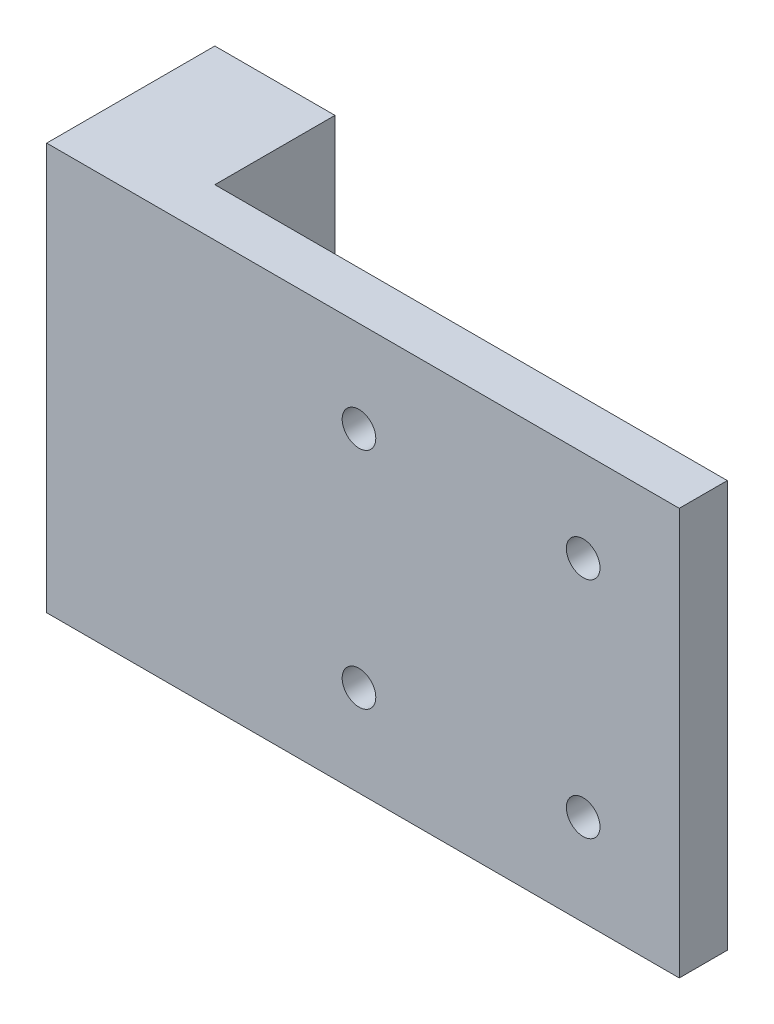
SolidWorks part; units mm, degrees
ref_plane "Front Plane" through (0, 0, 0) normal (0, 0, 1) x (1, 0, 0)
ref_plane "Top Plane" through (0, 0, 0) normal (0, 1, 0) x (1, 0, 0)
ref_plane "Right Plane" through (0, 0, 0) normal (1, 0, 0) x (0, 0, -1)
sketch "Sketch1" plane through (0, 0, 0) normal (0, 0, 1) x (1, 0, 0)
  line L1 (0, 0) -> (79, 0)
  line L2 (0, 0) -> (0, 50.8)
  line L3 (0, 50.8) -> (79, 50.8)
  line L4 (79, 0) -> (79, 50.8)
  circle A0 centre (67, 39.4) radius 2.1
  circle A1 centre (67, 11.4) radius 2.1
  circle A2 centre (39, 39.4) radius 2.1
  circle A3 centre (39, 11.4) radius 2.1
  dimension "D4" = 4.2
  dimension "D5" = 4.2
  dimension "D8" = 4.2
  dimension "D9" = 4.2
  dimension "D1" = 50.8
  dimension "D2" = 79
  dimension "D3" = 12
  dimension "D6" = 28
  dimension "D7" = 11.4
  dimension "D10" = 28
  dimension "D11" = 11.4
  dimension "D12" = 28
extrude "Boss-Extrude1" add sketch "Sketch1" along normal blind 6
sketch "Sketch3" plane through (0, 0, 0) normal (0, 0, -1) x (-1, 0, 0)
  line L0 (-79, 0) -> (-79, 50.8) construction
  line L1 (-15, 50.8) -> (0, 50.8)
  line L2 (-15, 50.8) -> (-15, 0)
  line L3 (-15, 0) -> (0, 0)
  line L4 (0, 50.8) -> (0, 0)
  line L5 (-79, 50.8) -> (0, 50.8) construction
  line L6 (0, 0) -> (-79, 0) construction
  dimension "D1" = 15
  dimension "D2" = 64
  dimension "D3" = 0
  dimension "D4" = 0
extrude "Boss-Extrude2" add sketch "Sketch3" along normal blind 15
equation "\"D5@Sketch1\"=\"D4@Sketch1\""
equation "\"D8@Sketch1\"=\"D4@Sketch1\""
equation "\"D9@Sketch1\"=\"D4@Sketch1\""
equation "\"D10@Sketch1\"=\"D6@Sketch1\""
equation "\"D11@Sketch1\"=\"D7@Sketch1\""
